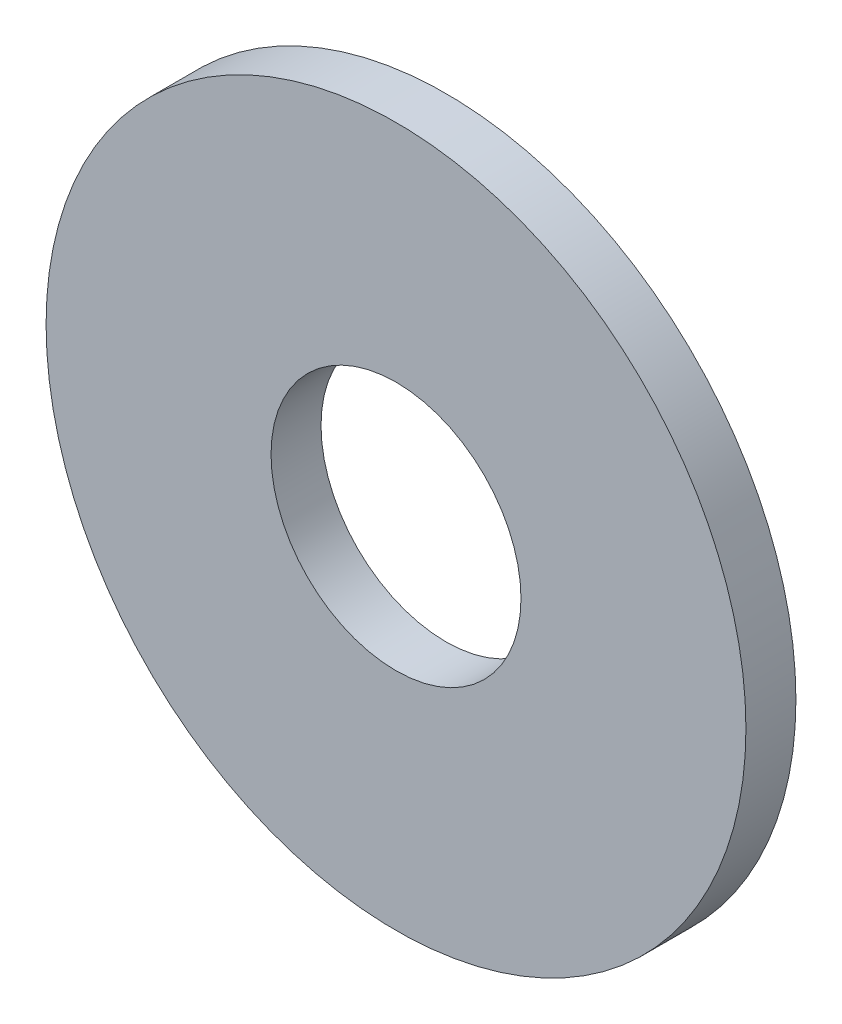
SolidWorks part; units mm, degrees
material "ASTM A36 Steel"
ref_plane "Front Plane" through (0, 0, 0) normal (0, 0, 1) x (1, 0, 0)
ref_plane "Top Plane" through (0, 0, 0) normal (0, 1, 0) x (1, 0, 0)
ref_plane "Right Plane" through (0, 0, 0) normal (1, 0, 0) x (0, 0, -1)
sketch "Sketch1" plane through (0, 0, 0) normal (0, 0, 1) x (1, 0, 0)
  circle A0 centre (0, 0) radius 14
  circle A1 centre (0, 0) radius 5
extrude "Boss-Extrude1" add sketch "Sketch1" along normal blind 2
